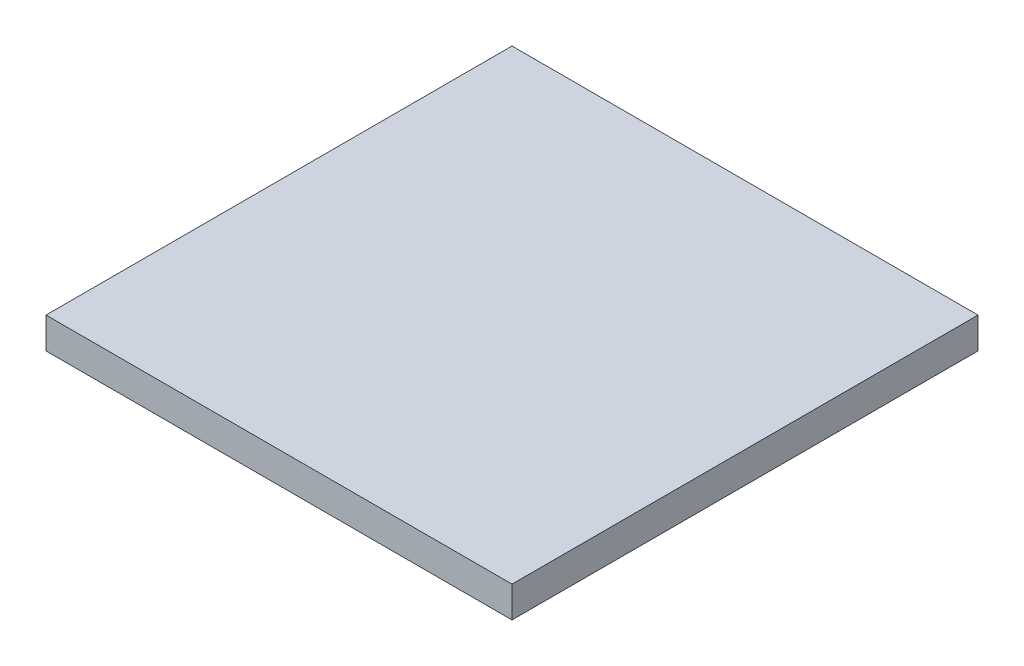
SolidWorks part; units mm, degrees
ref_plane "Alzado" through (0, 0, 0) normal (0, 0, 1) x (1, 0, 0)
ref_plane "Planta" through (0, 0, 0) normal (0, 1, 0) x (1, 0, 0)
ref_plane "Vista lateral" through (0, 0, 0) normal (1, 0, 0) x (0, 0, -1)
sketch "Croquis1" plane through (0, 0, 0) normal (0, 1, 0) x (1, 0, 0)
  line L1 (75, -75) -> (-75, -75)
  line L2 (75, -75) -> (75, 75)
  line L3 (75, 75) -> (-75, 75)
  line L4 (-75, -75) -> (-75, 75)
  line L5 (75, -75) -> (-75, 75) construction
  line L6 (75, 75) -> (-75, -75) construction
  point P0 (0, 0)
  dimension "D1" = 150
  dimension "D2" = 150
extrude "Saliente-Extruir1" add sketch "Croquis1" along normal blind 10
